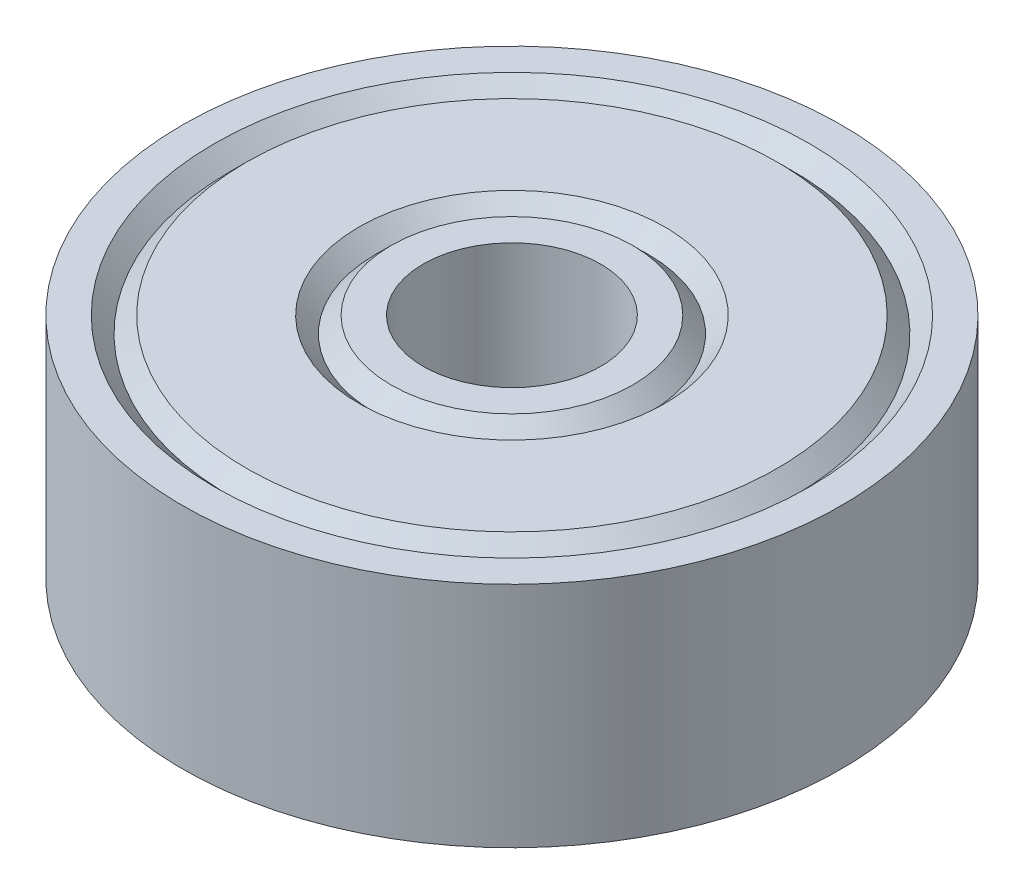
SolidWorks part; units mm, degrees
ref_plane "Front Plane" through (0, 0, 0) normal (0, 0, 1) x (1, 0, 0)
ref_plane "Top Plane" through (0, 0, 0) normal (0, 1, 0) x (1, 0, 0)
ref_plane "Right Plane" through (0, 0, 0) normal (1, 0, 0) x (0, 0, -1)
sketch "Sketch1" plane through (0, 0, 0) normal (0, 0, 1) x (1, 0, 0)
  line L0 (0, 4.5) -> (0, -4.5) construction
  line L1 (-3.5, 4.5) -> (-4.7667, 4.5)
  line L2 (-3.5, 4.5) -> (-3.5, -4.5)
  line L3 (-3.5, -4.5) -> (-4.7667, -4.5)
  line L4 (-13, 4.5) -> (-13, -4.5)
  line L5 (-11.7333, 4.5) -> (-11.1, 3.8667)
  line L6 (-11.1, 3.8667) -> (-10.4667, 4.5)
  line L7 (-6.0333, 4.5) -> (-5.4, 3.8667)
  line L8 (-5.4, 3.8667) -> (-4.7667, 4.5)
  line L9 (-11.7333, -4.5) -> (-11.1, -3.8667)
  line L10 (-11.1, -3.8667) -> (-10.4667, -4.5)
  line L11 (-6.0333, -4.5) -> (-5.4, -3.8667)
  line L12 (-5.4, -3.8667) -> (-4.7667, -4.5)
  line L13 (-6.0333, -4.5) -> (-10.4667, -4.5)
  line L14 (-11.7333, -4.5) -> (-13, -4.5)
  line L15 (-11.7333, 4.5) -> (-13, 4.5)
  line L16 (-6.0333, 4.5) -> (-10.4667, 4.5)
  line L17 (-11.1, 3.8667) -> (-5.4, 3.8667) construction
  line L18 (-11.1, 3.8667) -> (-11.1, -3.8667) construction
  line L19 (-5.4, -3.8667) -> (-11.1, -3.8667) construction
  line L20 (-5.4, 3.8667) -> (-5.4, -3.8667) construction
  line L21 (-11.1, 0) -> (-9.2, 0) construction
  line L22 (-4.7667, 4.5) -> (-6.0333, 4.5) construction
  line L23 (-9.2, 0) -> (-7.3, 0) construction
  line L24 (-11.1, 0) -> (-13, 0) construction
  line L25 (-7.3, 0) -> (-5.4, 0) construction
  line L26 (-5.4, 0) -> (-3.5, 0) construction
  dimension "D1" = 9
  dimension "D2" = 7
  dimension "D3" = 26
revolve "Revolve1" add sketch "Sketch1" angle 360 about L0
